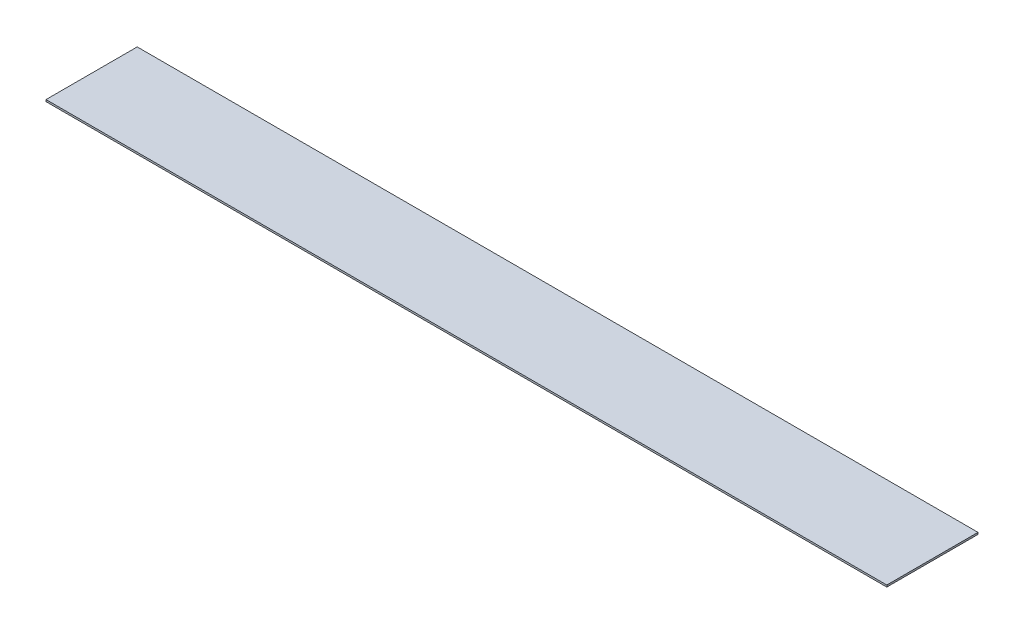
SolidWorks part; units mm, degrees
ref_plane "前视基准面" through (0, 0, 0) normal (0, 0, 1) x (1, 0, 0)
ref_plane "上视基准面" through (0, 0, 0) normal (0, 1, 0) x (1, 0, 0)
ref_plane "右视基准面" through (0, 0, 0) normal (1, 0, 0) x (0, 0, -1)
sketch "草图1" plane through (0, 0, 0) normal (0, 1, 0) x (1, 0, 0)
  line L1 (-461, 100) -> (461, 100)
  line L2 (-461, 100) -> (-461, 0)
  line L3 (-461, 0) -> (461, 0)
  line L4 (461, 100) -> (461, 0)
  point P4 (0, 0)
  dimension "D1" = 100
  dimension "D2" = 922
extrude "凸台-拉伸1" add sketch "草图1" along normal blind 2
